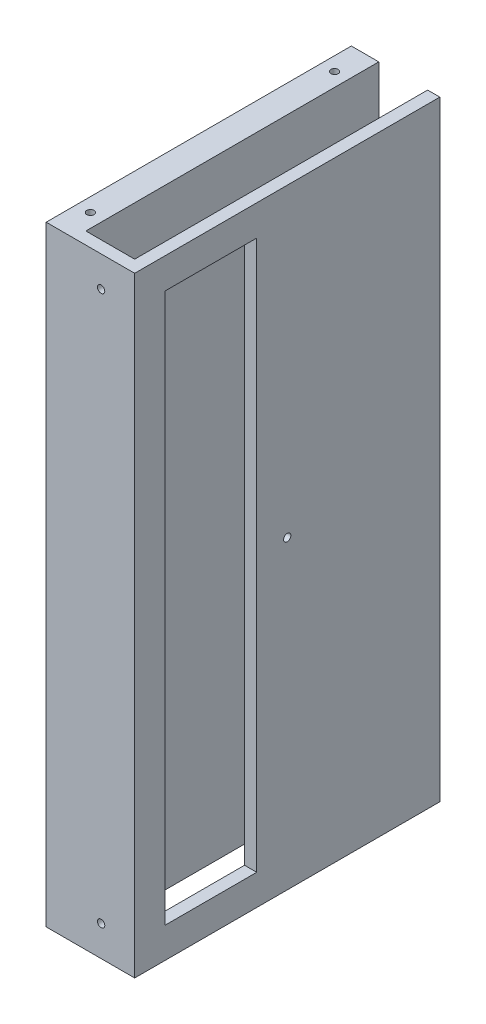
SolidWorks part; units mm, degrees
ref_plane "Front Plane" through (0, 0, 0) normal (0, 0, 1) x (1, 0, 0)
ref_plane "Top Plane" through (0, 0, 0) normal (0, 1, 0) x (1, 0, 0)
ref_plane "Right Plane" through (0, 0, 0) normal (1, 0, 0) x (0, 0, -1)
sketch "Sketch1" plane through (0, 0, 0) normal (0, 1, 0) x (1, 0, 0)
  line L1 (-14.5, 50) -> (14.5, 50)
  line L2 (-14.5, 50) -> (-14.5, -50)
  line L3 (-14.5, -50) -> (14.5, -50)
  line L4 (14.5, 50) -> (14.5, -50)
  line L5 (-14.5, 50) -> (14.5, -50) construction
  line L6 (-14.5, -50) -> (14.5, 50) construction
  point P0 (0, 0)
  dimension "D1" = 100
  dimension "D2" = 29
extrude "Boss-Extrude1" add sketch "Sketch1" along normal blind 200
sketch "Sketch2" plane through (0, 200, 0) normal (0, 1, 0) x (1, 0, 0)
  line L0 (14.5, 50) -> (-14.5, 50) construction
  line L1 (10.5, 50) -> (-5.5, 50)
  line L2 (10.5, 50) -> (10.5, -46)
  line L3 (10.5, -46) -> (-5.5, -46)
  line L4 (-5.5, 50) -> (-5.5, -46)
  line L5 (14.5, -50) -> (14.5, 50) construction
  line L6 (-14.5, -50) -> (14.5, -50) construction
  dimension "D1" = 4
  dimension "D2" = 16
  dimension "D3" = 4
extrude "Cut-Extrude1" cut sketch "Sketch2" against normal through all
sketch "Sketch3" plane through (14.5, 0, 0) normal (1, 0, 0) x (0, 0, -1)
  line L0 (-50, 0) -> (50, 0) construction
  line L1 (-40, 190) -> (-10, 190)
  line L2 (-40, 190) -> (-40, 10)
  line L3 (-40, 10) -> (-10, 10)
  line L4 (-10, 190) -> (-10, 10)
  line L5 (-50, 200) -> (-50, 0) construction
  line L6 (-50, 200) -> (50, 200) construction
  dimension "D1" = 10
  dimension "D2" = 10
  dimension "D3" = 10
  dimension "D4" = 30
extrude "Cut-Extrude2" cut sketch "Sketch3" along direction (-1, 0, 0) on the side against the normal up to surface (4 mm away)
hole_wizard "M2 Clearance Hole1" positions "Sketch5" profile "Sketch4" hole size "M2" standard "ANSI Metric"
sketch "Sketch5" plane through (0, 200, 0) normal (0, 1, 0) x (1, 0, 0)
  line L0 (-14.5, 50) -> (-14.5, -50) construction
  line L1 (-5.5, 50) -> (-14.5, 50) construction
  point P0 (-10, 40)
  point P2 (-10, -40)
  dimension "D1" = 4.5
  dimension "D2" = 4.5
  dimension "D3" = 10
  dimension "D4" = 80
sketch "Sketch4" plane through (-10, 200, -40) normal (1, 0, 0) x (0, 0, 1)
  line L0 (0, 0) -> (0, 11.921)
  line L1 (0, 11.921) -> (1.2, 11.2)
  line L2 (1.2, 11.2) -> (1.2, 0)
  line L5 (1.2, 0) -> (0, 0)
  line L10 (0, 11.921) -> (-1.2, 11.2) construction
  line L11 (0, -6.35) -> (0, 107.95) construction
  dimension "Hole Dia." = 2.4
  dimension "Hole Depth" = 11.2
  dimension "Drill Angle" = 118
hole_wizard "M2 Clearance Hole2" positions "Sketch7" profile "Sketch6" hole size "M2" standard "ANSI Metric"
sketch "Sketch7" plane through (0, 0, 0) normal (0, -1, 0) x (-1, 0, 0)
  line L0 (14.5, 50) -> (14.5, -50) construction
  line L1 (5.5, 50) -> (14.5, 50) construction
  point P0 (10, 40)
  point P2 (10, -40)
  point P8 (10, 50)
  dimension "D1" = 4.5
  dimension "D2" = 4.5
  dimension "D3" = 10
  dimension "D4" = 80
sketch "Sketch6" plane through (-10, 0, -40) normal (1, 0, 0) x (0, 0, -1)
  line L0 (0, 0) -> (0, 11.921)
  line L1 (0, 11.921) -> (1.2, 11.2)
  line L2 (1.2, 11.2) -> (1.2, 0)
  line L5 (1.2, 0) -> (0, 0)
  line L10 (0, 11.921) -> (-1.2, 11.2) construction
  line L11 (0, -6.35) -> (0, 107.95) construction
  dimension "Hole Dia." = 2.4
  dimension "Hole Depth" = 11.2
  dimension "Drill Angle" = 118
hole_wizard "M2 Clearance Hole3" positions "Sketch9" profile "Sketch8" hole size "M2" standard "ANSI Metric"
sketch "Sketch9" plane through (-14.5, 0, 0) normal (-1, 0, 0) x (0, 0, 1)
  line L1 (-50, 200) -> (50, 200) construction
  line L2 (-50, 0) -> (50, 0) construction
  line L3 (-50, 200) -> (-50, 0) construction
  line L4 (50, 200) -> (50, 0) construction
  point P0 (-30, 180)
  point P2 (-30, 20)
  point P4 (30, 100)
  dimension "D1" = 20
  dimension "D2" = 20
  dimension "D3" = 20
  dimension "D4" = 20
  dimension "D5" = 20
  dimension "D6" = 100
sketch "Sketch8" plane through (-14.5, 180, -30) normal (0, 1, 0) x (0, 0, 1)
  line L0 (0, 0) -> (0, 9.72)
  line L1 (0, 9.72) -> (1.2, 8.999)
  line L2 (1.2, 8.999) -> (1.2, 0)
  line L5 (1.2, 0) -> (0, 0)
  line L10 (0, 9.72) -> (-1.2, 8.999) construction
  line L11 (0, -6.35) -> (0, 107.95) construction
  dimension "Hole Dia." = 2.4
  dimension "Hole Depth" = 8.999
  dimension "Drill Angle" = 118
hole_wizard "M2 Clearance Hole4" positions "Sketch11" profile "Sketch10" hole size "M2" standard "ANSI Metric"
sketch "Sketch11" plane through (14.5, 0, 0) normal (1, 0, 0) x (0, 0, -1)
  line L0 (-50, 0) -> (50, 0) construction
  point P0 (0, 100)
  dimension "D1" = 100
sketch "Sketch10" plane through (14.5, 100, 0) normal (0, 1, 0) x (0, 0, -1)
  line L0 (0, 0) -> (0, 4.72)
  line L1 (0, 4.72) -> (1.2, 3.999)
  line L2 (1.2, 3.999) -> (1.2, 0)
  line L5 (1.2, 0) -> (0, 0)
  line L10 (0, 4.72) -> (-1.2, 3.999) construction
  line L11 (0, -6.35) -> (0, 107.95) construction
  dimension "Hole Dia." = 2.4
  dimension "Hole Depth" = 3.999
  dimension "Drill Angle" = 118
hole_wizard "M2 Clearance Hole5" positions "Sketch13" profile "Sketch12" hole size "M2" standard "ANSI Metric" end condition through all
sketch "Sketch13" plane through (0, 0, 50) normal (0, 0, 1) x (1, 0, 0)
  line L0 (-14.5, 200) -> (14.5, 200) construction
  line L1 (-14.5, 0) -> (14.5, 0) construction
  line L2 (14.5, 200) -> (14.5, 0) construction
  point P0 (3.5, 10)
  point P2 (3.5, 190)
  dimension "D1" = 10
  dimension "D2" = 10
  dimension "D3" = 11
  dimension "D4" = 11
sketch "Sketch12" plane through (3.5, 10, 50) normal (1, 0, 0) x (0, -1, 0)
  line L0 (0, 0) -> (0, 100)
  line L1 (0, 100) -> (1.2, 100)
  line L2 (1.2, 100) -> (1.2, 0)
  line L5 (1.2, 0) -> (0, 0)
  line L11 (0, -6.35) -> (0, 107.95) construction
  dimension "Thru Hole Dia." = 2.4
  dimension "Thru Hole Depth" = 100
